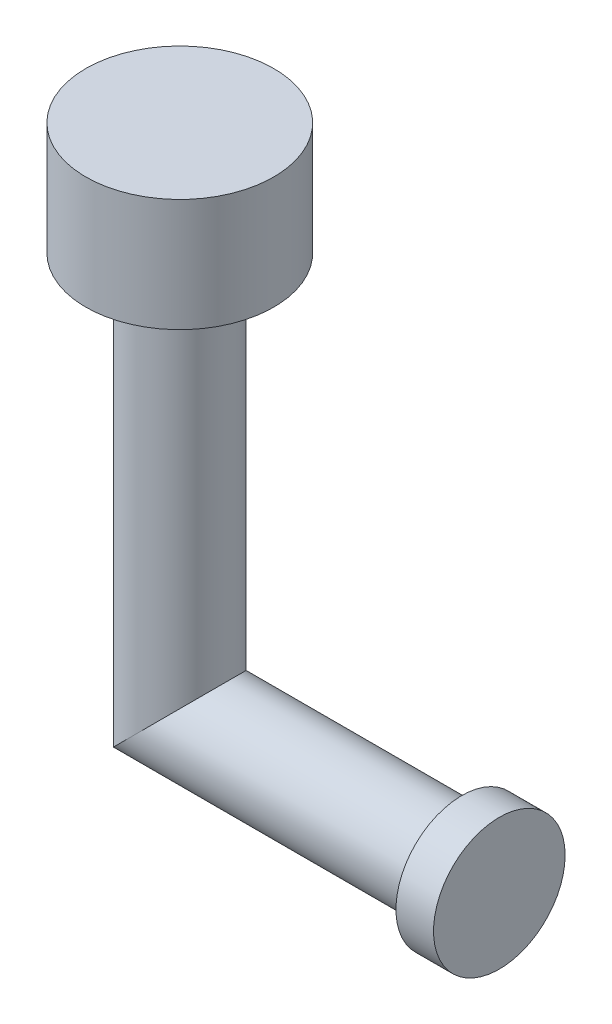
SolidWorks part; units mm, degrees
ref_plane "Front Plane" through (0, 0, 0) normal (0, 0, 1) x (1, 0, 0)
ref_plane "Top Plane" through (0, 0, 0) normal (0, 1, 0) x (1, 0, 0)
ref_plane "Right Plane" through (0, 0, 0) normal (1, 0, 0) x (0, 0, -1)
sketch "Sketch1" plane through (0, 0, 0) normal (0, 0, 1) x (1, 0, 0)
  line L0 (0, 0) -> (0, 21)
  line L1 (0, 0) -> (15, 0)
  dimension "D1" = 21
  dimension "D2" = 15
ref_plane "Plane1" through (15, 0, 0) normal (1, 0, 0) x (0, 0, -1)
sketch "Sketch2" plane through (15, 0, 0) normal (1, 0, 0) x (0, 0, -1)
  circle A0 centre (0, 0) radius 2.5
  dimension "D1" = 5
sweep "Sweep1" add profiles "Sketch2" path "Sketch1"
sketch "Sketch3" plane through (15, 0, 0) normal (1, 0, 0) x (0, 0, -1)
  circle A0 centre (0, 0) radius 3.5
  dimension "D1" = 7
extrude "Boss-Extrude1" add sketch "Sketch3" along normal blind 2
sketch "Sketch4" plane through (0, 21, 0) normal (0, 1, 0) x (1, 0, 0)
  circle A0 centre (0, 0) radius 5
  dimension "D1" = 10
extrude "Boss-Extrude2" add sketch "Sketch4" along normal blind 6
